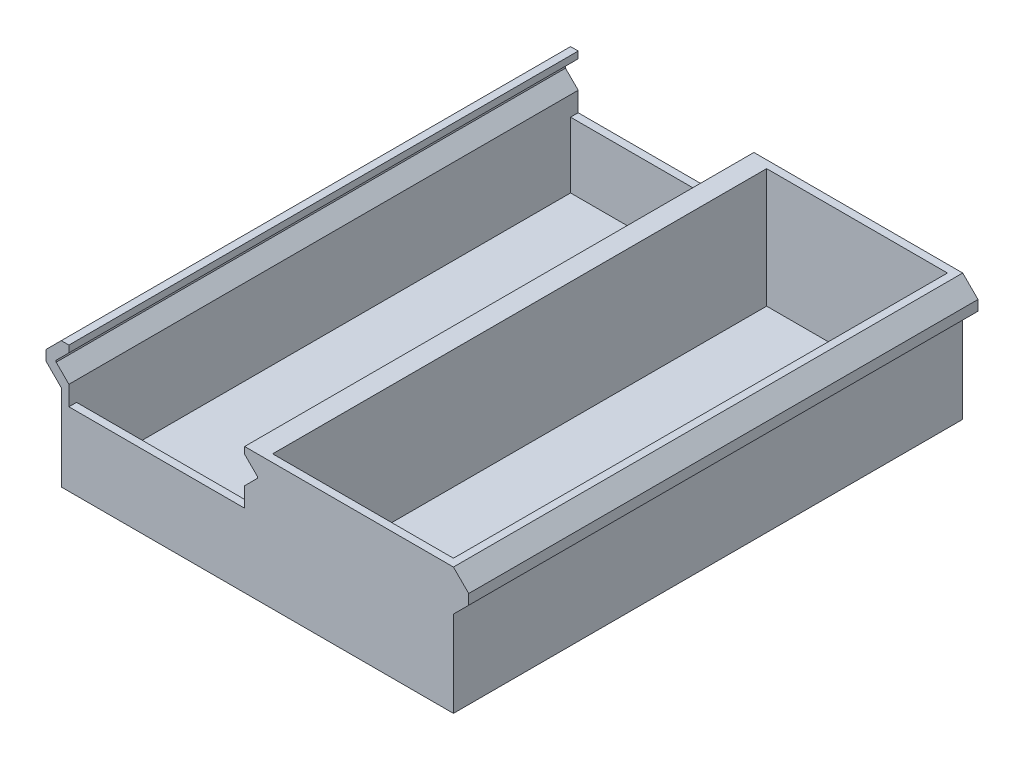
SolidWorks part; units mm, degrees
ref_plane "前视基准面" through (0, 0, 0) normal (0, 0, 1) x (1, 0, 0)
ref_plane "上视基准面" through (0, 0, 0) normal (0, 1, 0) x (1, 0, 0)
ref_plane "右视基准面" through (0, 0, 0) normal (1, 0, 0) x (0, 0, -1)
sketch "草图1" plane through (0, 0, 0) normal (0, 0, 1) x (1, 0, 0)
  line L0 (77, 0) -> (-77, 0)
  line L1 (-77, 0) -> (-77, 33.779)
  line L2 (-77, 33.779) -> (-83, 39.779)
  line L3 (-83, 39.779) -> (-83, 43.779)
  line L4 (-83, 43.779) -> (-77, 49.779)
  line L5 (-77, 49.779) -> (77, 49.779)
  line L6 (0, 49.779) -> (0, 0) construction
  line L7 (83, 43.779) -> (77, 49.779)
  line L8 (83, 39.779) -> (83, 43.779)
  line L9 (77, 33.779) -> (83, 39.779)
  line L10 (77, 0) -> (77, 33.779)
  point P10 (0, 0)
  point P12 (0, 49.779)
  point P16 (0, 0)
  dimension "D1" = 77
  dimension "D2" = 49.779
  dimension "D3" = 45
  dimension "D4" = 45
  dimension "D5" = 6
  dimension "D6" = 16
extrude "凸台-拉伸1" add sketch "草图1" against normal blind 200 contours L5 L7 L8 L9 L10 L0 L1 L2 L3 L4
sketch "草图2" plane through (0, 49.779, 0) normal (0, 1, 0) x (1, 0, 0)
  line L8 (-74, 3) -> (74, 3)
  line L9 (74, 3) -> (74, 197)
  line L10 (74, 197) -> (-74, 197)
  line L11 (-74, 197) -> (-74, 3)
  line L12 (-74, 3) -> (74, 3)
  line L13 (74, 3) -> (74, 197)
  line L14 (74, 197) -> (-74, 197)
  line L15 (-74, 197) -> (-74, 3)
  dimension "D1" = 3
extrude "切除-拉伸1" cut sketch "草图2" along direction (0, -1, 0) on the side against the normal offset from surface (46.779 mm away) 3
sketch "草图3" plane through (0, 3, 0) normal (0, 1, 0) x (1, 0, 0)
  line L0 (-74, 3) -> (74, 3) construction
  line L1 (0, 3) -> (0, 197)
  line L2 (74, 197) -> (-74, 197) construction
extrude "拉伸-薄壁1" add sketch "草图3" along normal up to surface (46.779 mm away) thin
sketch "草图4" plane through (0, 0, 0) normal (0, 0, 1) x (1, 0, 0)
  line L0 (-74, 49.779) -> (-74, 47.1222)
  line L1 (-77, 49.779) -> (77, 49.779) construction
  line L2 (-74, 47.1222) -> (-79, 42.1222)
  line L3 (-79, 42.1222) -> (-79, 41.4359)
  line L4 (-79, 41.4359) -> (-74, 36.4359)
  line L5 (-74, 36.4359) -> (-74, 28.779)
  line L6 (-74, 28.779) -> (-5, 28.779)
  line L7 (-5, 28.779) -> (-5, 36.4359)
  line L8 (-5, 36.4359) -> (0, 41.4359)
  line L9 (0, 41.4359) -> (0, 42.1222)
  line L10 (0, 42.1222) -> (-5, 47.1222)
  line L11 (-5, 47.1222) -> (-5, 49.779)
  line L12 (-5, 49.779) -> (-74, 49.779)
  line L13 (-74, 3) -> (-74, 49.779) construction
  line L14 (-78, 40.4359) -> (-73, 35.4359) construction
  line L15 (-78, 41.7079) -> (-78, 40.4359) construction
  line L16 (-73, 46.7079) -> (-78, 41.7079) construction
  line L17 (-73, 30.779) -> (-6, 30.779) construction
  line L18 (-5, 49.779) -> (-5, 3) construction
  line L19 (-6, 35.4359) -> (-1, 40.4359) construction
  line L21 (-1, 40.4359) -> (-1, 41.7079) construction
  line L22 (-1, 41.7079) -> (-6, 46.7079) construction
  point P24 (-3.1455, 46.5708)
  dimension "D1" = 1
  dimension "D2" = 1
  dimension "D3" = 2
  dimension "D4" = 1
  dimension "D5" = 1
extrude "切除-拉伸2" cut sketch "草图4" against normal through all
